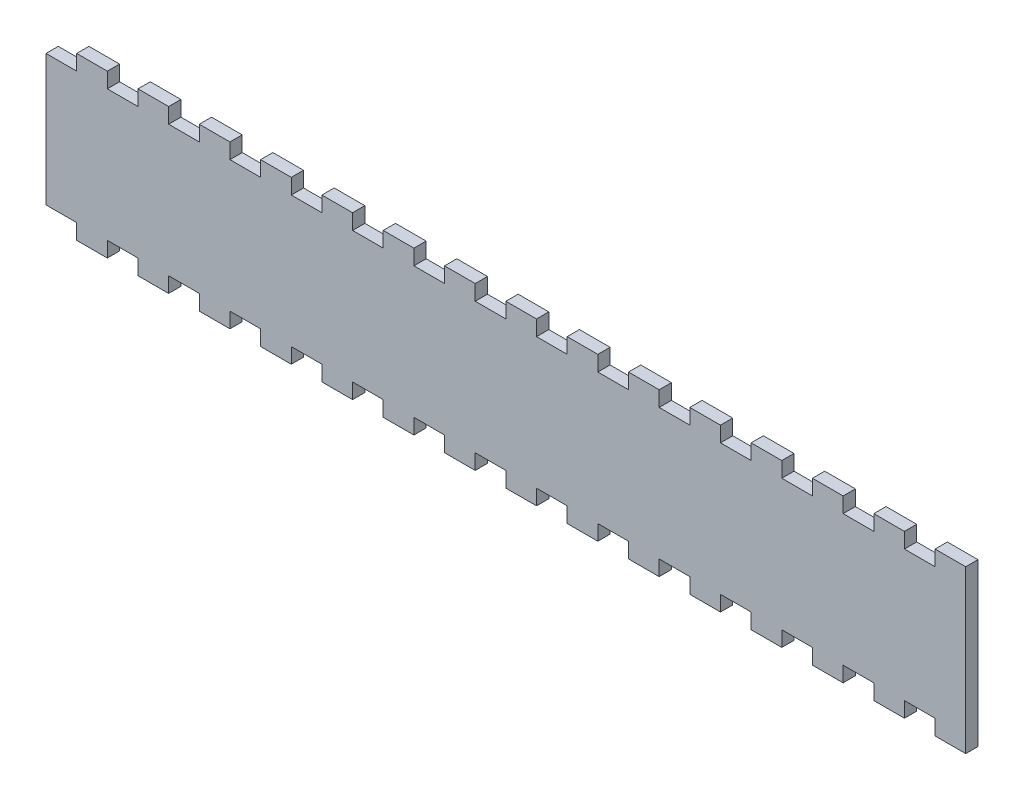
SolidWorks part; units mm, degrees
ref_plane "Front Plane" through (0, 0, 0) normal (0, 0, 1) x (1, 0, 0)
ref_plane "Top Plane" through (0, 0, 0) normal (0, 1, 0) x (1, 0, 0)
ref_plane "Right Plane" through (0, 0, 0) normal (1, 0, 0) x (0, 0, -1)
sketch "Sketch1" plane through (0, 0, 0) normal (0, 0, 1) x (1, 0, 0)
  line L0 (0, 10.7) -> (150, 10.7) construction
  line L1 (0, 0) -> (150, 0)
  line L2 (0, 0) -> (0, 21.4)
  line L3 (0, 21.4) -> (150, 21.4)
  line L4 (150, 0) -> (150, 21.4)
  dimension "D5" = 21.4
  dimension "D8" = 150
extrude "Boss-Extrude2" add sketch "Sketch1" along normal blind 2
sketch "Sketch2" plane through (0, 21.4, 0) normal (0, 1, 0) x (1, 0, 0)
  line L1 (0, 0) -> (150, 0) construction
  line L2 (5, 0) -> (10, 0)
  line L3 (5, 0) -> (5, -2)
  line L4 (5, -2) -> (10, -2)
  line L5 (10, 0) -> (10, -2)
  line L6 (0, -2) -> (150, -2) construction
  line L7 (0, -2) -> (0, 0) construction
  dimension "D1" = 5
  dimension "D2" = 5
extrude "Boss-Extrude3" add sketch "Sketch2" along normal blind 2.5
pattern_linear "LPattern1" count 15 spacing 10 along (1, 0, 0) of "Boss-Extrude3"
sketch "Sketch3" plane through (0, 0, 0) normal (0, -1, 0) x (-1, 0, 0)
  line L1 (0, -2) -> (-150, -2) construction
  line L2 (-5, -2) -> (-10, -2)
  line L3 (-5, -2) -> (-5, 0)
  line L4 (-5, 0) -> (-10, 0)
  line L5 (-10, -2) -> (-10, 0)
  line L6 (0, 0) -> (-150, 0) construction
  line L7 (0, -2) -> (0, 0) construction
  point P9 (0, -1)
  dimension "D1" = 5
  dimension "D2" = 5
extrude "Boss-Extrude4" add sketch "Sketch3" along normal blind 2.5
pattern_linear "LPattern2" count 15 spacing 10 along (1, 0, 0) of "Boss-Extrude4"
